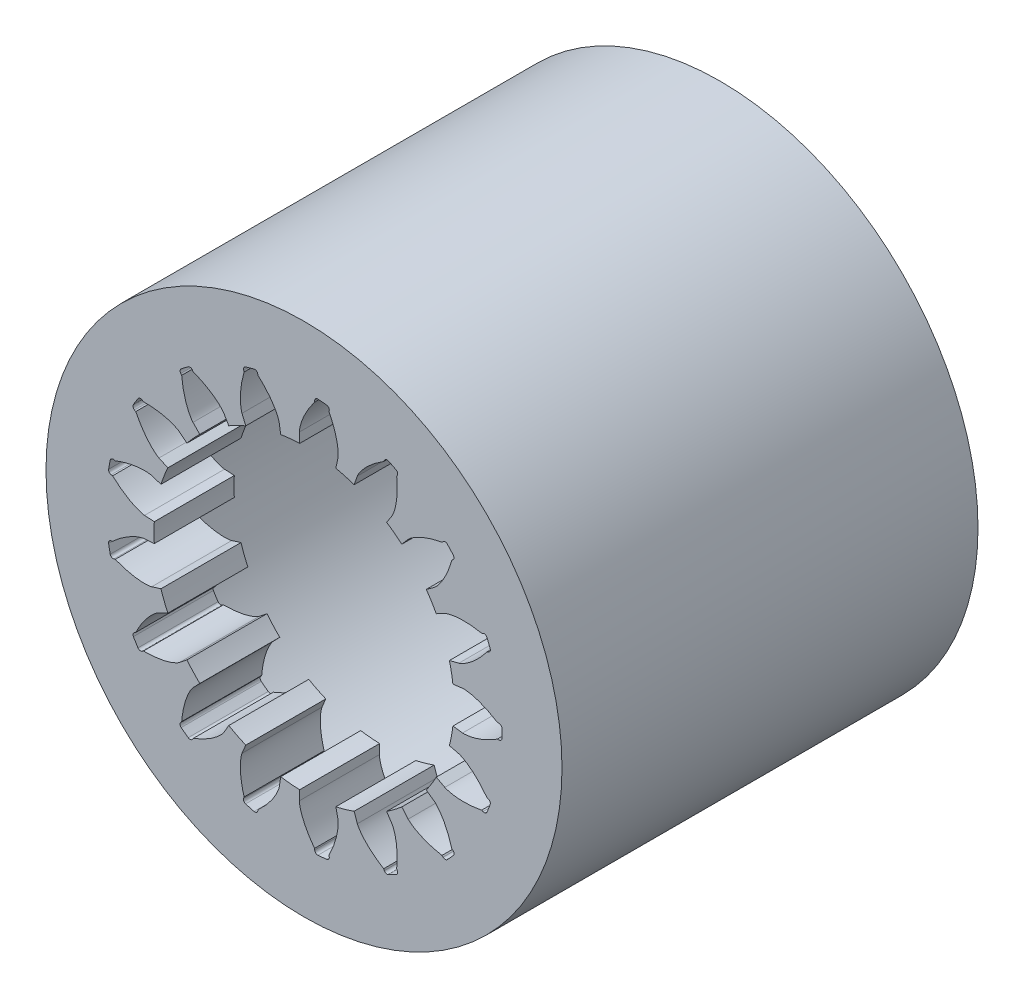
SolidWorks part; units mm, degrees
ref_plane "Front Plane" through (0, 0, 0) normal (0, 0, 1) x (1, 0, 0)
ref_plane "Top Plane" through (0, 0, 0) normal (0, 1, 0) x (1, 0, 0)
ref_plane "Right Plane" through (0, 0, 0) normal (1, 0, 0) x (0, 0, -1)
ref_axis "Gear Axis" through (0, 0, -1.3001) along (0, 0, 1)
sketch "Blank Sketch" plane through (0, 0, 0) normal (0, 0, 1) x (1, 0, 0)
  circle A0 centre (0, 0) radius 16.125
  circle A1 centre (0, 0) radius 9.375
  dimension "Rim" = 32.25
  dimension "Tip" = 18.75
extrude "Blank" add sketch "Blank Sketch" along normal blind 26
sketch "Tooth Space Sketch" plane through (0, 0, 0) normal (0, 0, 1) x (1, 0, 0)
  line L0 (9.9107, 1.2093) -> (8.0652, 0.9841)
  line L1 (9.9107, -1.2093) -> (8.0652, -0.9841)
  line L2 (8.0652, 0.9841) -> (8.0652, -0.9841)
  line L3 (12.0853, 0.4532) -> (12.1775, 0.4566)
  line L4 (12.0853, -0.4532) -> (12.1775, -0.4566)
  circle A0 centre (0, 0) radius 8.125 construction
  arc A1 (12.372, 0.2734) -> (12.1775, 0.4566) centre (12.1845, 0.2692) ccw
  arc A2 (12.1775, -0.4566) -> (12.372, -0.2734) centre (12.1845, -0.2692) ccw
  arc A3 (12.372, -0.2734) -> (12.372, 0.2734) centre (0, 0) ccw
  spline S0 degree 4 poles (9.9107, 1.2093) (9.9142, 1.2097) (9.9238, 1.2106) (9.9421, 1.2116) (9.9719, 1.2125) (10.0101, 1.2123) (10.0595, 1.2106) (10.1177, 1.2068) (10.1817, 1.2005) (10.2513, 1.1916) (10.3207, 1.1809) (10.3898, 1.1685) (10.4586, 1.1545) (10.5417, 1.1357) (10.6413, 1.1106) (10.7572, 1.0776) (10.8882, 1.0357) (11.021, 0.9883) (11.1511, 0.9379) (11.2818, 0.8826) (11.4077, 0.826) (11.5375, 0.7627) (11.6569, 0.7021) (11.7895, 0.6293) (11.8961, 0.5691) (12.0355, 0.4846) (12.1174, 0.4332) (12.2128, 0.3713) (12.2549, 0.3428) (12.2808, 0.3254) knots 0 0 0 0 0 0.005377 0.015084 0.028532 0.04661 0.064855 0.092111 0.119476 0.146842 0.174209 0.201575 0.228941 0.256307 0.307035 0.361767 0.4165 0.471232 0.525964 0.580697 0.635429 0.690161 0.744894 0.799626 0.854358 0.909091 0.954545 1 1 1 1 1 construction
  spline S1 degree 4 poles (9.9107, 1.2093) (9.9142, 1.2097) (9.9238, 1.2106) (9.9421, 1.2116) (9.9719, 1.2125) (10.0101, 1.2123) (10.0595, 1.2106) (10.1177, 1.2068) (10.1817, 1.2005) (10.2513, 1.1916) (10.3207, 1.1809) (10.3898, 1.1685) (10.4586, 1.1545) (10.5417, 1.1357) (10.6413, 1.1106) (10.7572, 1.0776) (10.8882, 1.0357) (11.021, 0.9883) (11.1511, 0.9379) (11.2818, 0.8826) (11.4077, 0.826) (11.5375, 0.7627) (11.6569, 0.7021) (11.7895, 0.6293) (11.8961, 0.5691) (12.0053, 0.503) (12.0583, 0.4702) (12.0853, 0.4532) knots 0 0 0 0 0 0.005377 0.015084 0.028532 0.04661 0.064855 0.092111 0.119476 0.146842 0.174209 0.201575 0.228941 0.256307 0.307035 0.361767 0.4165 0.471232 0.525964 0.580697 0.635429 0.690161 0.744894 0.799626 0.854358 0.909091 0.909091 0.909091 0.909091 0.909091
  spline S2 degree 4 poles (9.9107, -1.2093) (9.9142, -1.2097) (9.9238, -1.2106) (9.9421, -1.2116) (9.9719, -1.2125) (10.0101, -1.2123) (10.0595, -1.2106) (10.1177, -1.2068) (10.1817, -1.2005) (10.2513, -1.1916) (10.3207, -1.1809) (10.3898, -1.1685) (10.4586, -1.1545) (10.5417, -1.1357) (10.6413, -1.1106) (10.7572, -1.0776) (10.8882, -1.0357) (11.021, -0.9883) (11.1511, -0.9379) (11.2818, -0.8826) (11.4077, -0.826) (11.5375, -0.7627) (11.6569, -0.7021) (11.7895, -0.6293) (11.8961, -0.5691) (12.0355, -0.4846) (12.1174, -0.4332) (12.2128, -0.3713) (12.2549, -0.3428) (12.2808, -0.3254) knots 0 0 0 0 0 0.005377 0.015084 0.028532 0.04661 0.064855 0.092111 0.119476 0.146842 0.174209 0.201575 0.228941 0.256307 0.307035 0.361767 0.4165 0.471232 0.525964 0.580697 0.635429 0.690161 0.744894 0.799626 0.854358 0.909091 0.954545 1 1 1 1 1 construction
  spline S3 degree 4 poles (9.9107, -1.2093) (9.9142, -1.2097) (9.9238, -1.2106) (9.9421, -1.2116) (9.9719, -1.2125) (10.0101, -1.2123) (10.0595, -1.2106) (10.1177, -1.2068) (10.1817, -1.2005) (10.2513, -1.1916) (10.3207, -1.1809) (10.3898, -1.1685) (10.4586, -1.1545) (10.5417, -1.1357) (10.6413, -1.1106) (10.7572, -1.0776) (10.8882, -1.0357) (11.021, -0.9883) (11.1511, -0.9379) (11.2818, -0.8826) (11.4077, -0.826) (11.5375, -0.7627) (11.6569, -0.7021) (11.7895, -0.6293) (11.8961, -0.5691) (12.0053, -0.503) (12.0583, -0.4702) (12.0853, -0.4532) knots 0 0 0 0 0 0.005377 0.015084 0.028532 0.04661 0.064855 0.092111 0.119476 0.146842 0.174209 0.201575 0.228941 0.256307 0.307035 0.361767 0.4165 0.471232 0.525964 0.580697 0.635429 0.690161 0.744894 0.799626 0.854358 0.909091 0.909091 0.909091 0.909091 0.909091
  dimension "Root" = 12.375
  dimension "Fillet" = 0.1875
  dimension "Cap" = 16.25
extrude "Tooth Space" cut sketch "Tooth Space Sketch" against normal through all both and the other way through all both
pattern_circular "Teeth" count 17 over 360 about axis through (0, 0, -1.3001) along (0, 0, 1) of "Tooth Space"
ref_plane "Relief Mid Plane" through (0, 0, 13) normal (0, 0, 1) x (1, 0, 0)
sketch "Relief Sketch" plane through (0, 0, 13) normal (0, 0, 1) x (1, 0, 0)
  circle A0 centre (0, 0) radius 13
extrude "Relief Bore" cut sketch "Relief Sketch" against normal mid plane 16
equation "\"No. of Teeth\"= 17"
equation "\"Module\"= 1.25"
equation "\"Pressure Angle\"= 20"
equation "\"Inner Diameter\"= ( \"No. of Teeth\" - 2 ) * \"Module\""
equation "\"Pitch Diameter\"= \"No. of Teeth\" * \"Module\""
equation "\"Backlash\" = IIF ( \"Module\" <= 1 , 0.3 * \"Module\" , 0.3 )"
equation "\"Arc Length\"= ( ( \"Module\" * pi ) / 2 + \"Backlash\" )"
equation "\"Fillet Radius\"= 0.15 * \"Module\""
equation "\"Tooth Depth\"= IIF ( \"Module\" <= 1.25 , \"Module\" * 2.4 , \"Module\" * 2.25 )"
equation "\"Face Width\"= 26"
equation "\"Root Diameter\"= \"Inner Diameter\" + 2 * \"Tooth Depth\""
equation "\"Rim Diameter\"= \"Root Diameter\" + 6 * \"Module\""
equation "\"Base Diameter\"= \"Pitch Diameter\" * cos ( \"Pressure Angle\" )"
equation "\"Base Radius\"= \"Base Diameter\" / 2"
equation "\"Tooth Thickness\"= \"Module\" * pi - \"Arc Length\""
equation "\"Half Space Angle\"= ( \"Arc Length\" / \"Pitch Diameter\" ) * 180 / pi"
equation "\"Involute Fn\"= tan ( \"Pressure Angle\" ) - \"Pressure Angle\" * pi / 180"
equation "\"Flank Offset\"= 0 - \"Arc Length\" / \"Pitch Diameter\" - \"Involute Fn\""
equation "\"Tip Cap Diameter\"= \"Inner Diameter\" - 2 * \"Module\""
equation "\"Flank Start Diameter\"= IIF ( \"Base Diameter\" >= ( \"Inner Diameter\" - \"Module\" ) , \"Base Diameter\" , \"Inner Diameter\" - \"Module\" )"
equation "\"Flank End Diameter\"= \"Root Diameter\" - 3 * \"Fillet Radius\""
equation "\"Involute t1\"= ( abs ( ( \"Flank Start Diameter\" / \"Base Diameter\" ) ^ 2 - 1 ) ) ^ 0.5"
equation "\"Involute t2\"= ( abs ( ( \"Flank End Diameter\" / \"Base Diameter\" ) ^ 2 - 1 ) ) ^ 0.5"
equation "\"Flank Arc Radius\"= ( \"Pitch Diameter\" / 2 ) * sin ( \"Pressure Angle\" )"
equation "\"Flank Centre Angle\"= \"Half Space Angle\" - \"Pressure Angle\""
equation "\"Rim@Blank Sketch\"= \"Rim Diameter\""
equation "\"Tip@Blank Sketch\"= \"Inner Diameter\""
equation "\"Width@Blank\"= \"Face Width\""
equation "\"Root@Tooth Space Sketch\"= \"Root Diameter\" / 2"
equation "\"Fillet@Tooth Space Sketch\"= \"Fillet Radius\""
equation "\"Cap@Tooth Space Sketch\"= \"Tip Cap Diameter\""
equation "\"Count@Teeth\"= \"No. of Teeth\""
